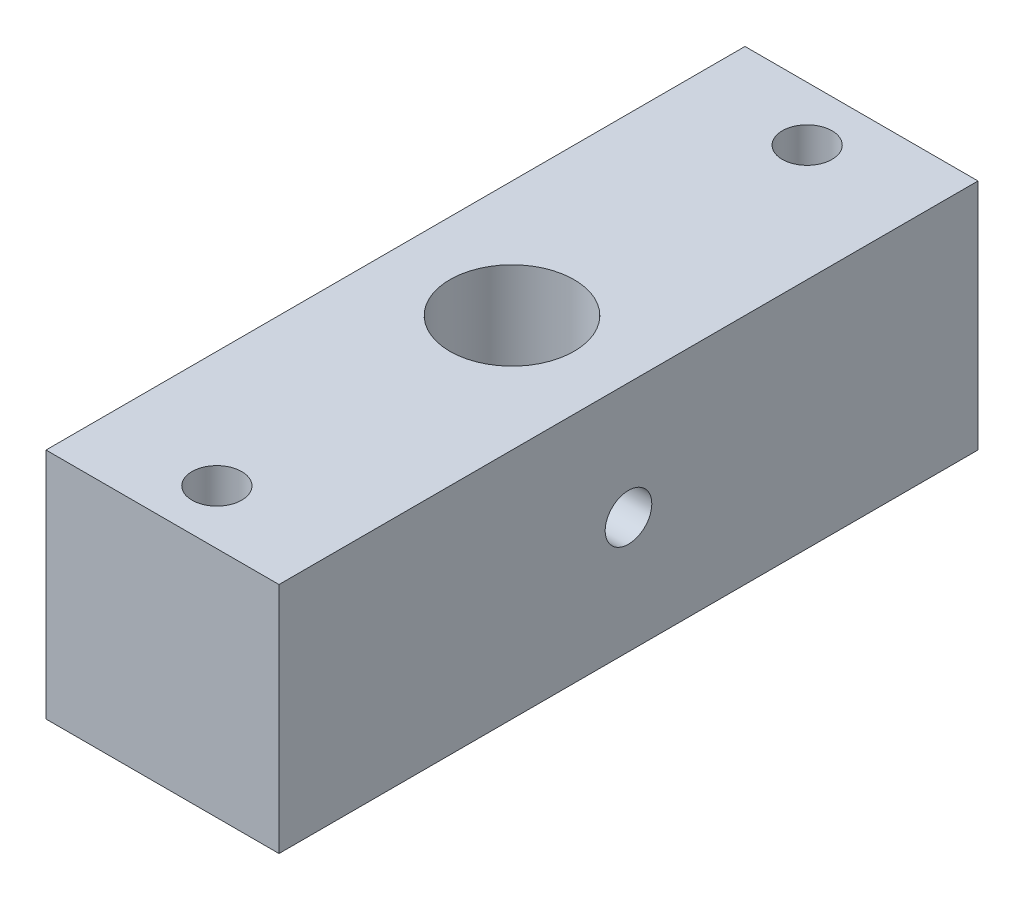
SolidWorks part; units mm, degrees
material "ABS"
ref_plane "前视基准面" through (0, 0, 0) normal (0, 0, 1) x (1, 0, 0)
ref_plane "上视基准面" through (0, 0, 0) normal (0, 1, 0) x (1, 0, 0)
ref_plane "右视基准面" through (0, 0, 0) normal (1, 0, 0) x (0, 0, -1)
sketch "草图1" plane through (0, 0, 0) normal (0, 1, 0) x (1, 0, 0)
  line L1 (-7.5, 22.5) -> (7.5, 22.5)
  line L2 (-7.5, 22.5) -> (-7.5, -22.5)
  line L3 (-7.5, -22.5) -> (7.5, -22.5)
  line L4 (7.5, 22.5) -> (7.5, -22.5)
  line L5 (0, -22.5) -> (0, 22.5) construction
  line L6 (-7.5, 0) -> (7.5, 0) construction
  circle A0 centre (0, 0) radius 4
  circle A1 centre (0, 19) radius 1.6
  circle A2 centre (0, -19) radius 1.6
  point P0 (0, 0)
  dimension "D3" = 8
  dimension "D4" = 3.2
  dimension "D1" = 45
  dimension "D2" = 15
  dimension "D5" = 38
extrude "凸台-拉伸1" add sketch "草图1" along normal mid plane 15
sketch "草图2" plane through (7.5, 0, 0) normal (1, 0, 0) x (0, 0, -1)
  circle A0 centre (0, 0) radius 1.5
  dimension "D1" = 3
extrude "切除-拉伸1" cut sketch "草图2" against normal through all
